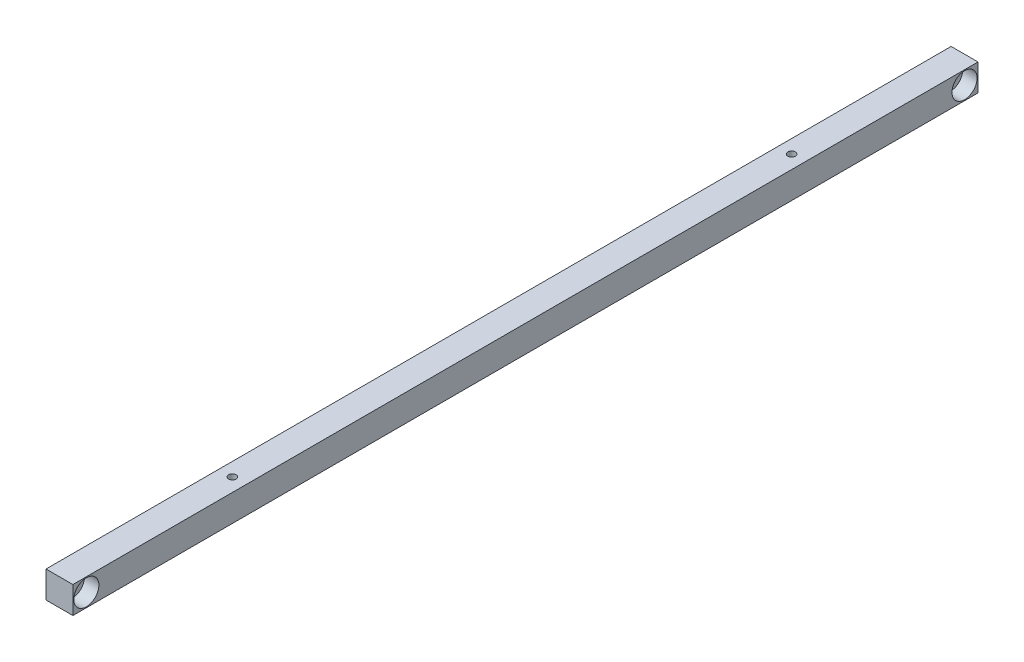
SolidWorks part; units mm, degrees
material "1.0715 (11SMn30)"
ref_plane "Ön Düzlem" through (0, 0, 0) normal (0, 0, 1) x (1, 0, 0)
ref_plane "Üst Düzlem" through (0, 0, 0) normal (0, 1, 0) x (1, 0, 0)
ref_plane "Sağ Düzlem" through (0, 0, 0) normal (1, 0, 0) x (0, 0, -1)
sketch "Çizim1" plane through (0, 0, 0) normal (0, 0, 1) x (1, 0, 0)
  line L1 (7.5, -7.5) -> (-7.5, -7.5)
  line L2 (7.5, -7.5) -> (7.5, 7.5)
  line L3 (7.5, 7.5) -> (-7.5, 7.5)
  line L4 (-7.5, -7.5) -> (-7.5, 7.5)
  line L5 (7.5, -7.5) -> (-7.5, 7.5) construction
  line L6 (7.5, 7.5) -> (-7.5, -7.5) construction
  point P0 (0, 0)
  dimension "D1" = 15
extrude "Yükseklik-Ekstrüzyon1" add sketch "Çizim1" along normal mid plane 505
hole_wizard "Delik1" positions "3B Çizim1" profile "Çizim4" legacy
sketch3d "3B Çizim1"
  line L1 (7.5, -7.5, 252.5) -> (7.5, -7.5, -252.5) construction
  line L2 (7.5, -7.5, -252.5) -> (7.5, 7.5, -252.5) construction
  point P21 (7.5, 0, -245)
  dimension "D1" = 7.5
  dimension "D2" = 7.5
sketch "Çizim4" plane through (7.5, 0, -245) normal (0, 1, 0) x (0, 0, -1)
  line L0 (0, 0) -> (0, 15)
  line L1 (0, 15) -> (4.25, 15)
  line L2 (4.25, 15) -> (4.25, 8)
  line L3 (4.25, 8) -> (7, 8)
  line L4 (7, 8) -> (7, 0)
  line L5 (7, 0) -> (0, 0)
  line L6 (0, 110) -> (0, -10) construction
  dimension "Diameter" = 8.5
  dimension "Depth" = 15
  dimension "C-Bore Diameter" = 14
  dimension "C-Bore Depth" = 8
mirror "Aynalama1" about plane through (0, 0, 0) normal (0, 0, 1) of "Delik1"
hole_wizard "M5 Dişli Delik1" positions "Çizim5" profile "Çizim6" tap size "M5" standard "ISO"
sketch "Çizim5" plane through (0, -7.5, 0) normal (0, -1, 0) x (-1, 0, 0)
  line L0 (0, 0) -> (40.6786, 0) construction
  point P0 (0, 155.9964)
  point P7 (0, -155.9964)
sketch "Çizim6" plane through (0, -7.5, -155.9964) normal (1, 0, 0) x (0, 0, -1)
  line L0 (0, 0) -> (0, 25.2618)
  line L1 (0, 25.2618) -> (2.1, 24)
  line L2 (2.1, 24) -> (2.1, 0.425)
  line L3 (2.1, 0.425) -> (2.525, 0)
  line L5 (2.525, 0) -> (0, 0)
  line L6 (-2.1, 0.425) -> (-2.525, 0) construction
  line L10 (0, 25.2618) -> (-2.1, 24) construction
  line L11 (0, -6.35) -> (0, 107.95) construction
  dimension "Tap Drill Dia." = 4.2
  dimension "Tap Drill Depth" = 24
  dimension "Near C'Sink Dia." = 5.05
  dimension "Near C'Sink Angle" = 90
  dimension "Drill Angle" = 118
cosmetic thread "Delik Dişi1" parameters "D1"=20, "D2"=5
cosmetic thread "Delik Dişi2" parameters "D1"=20, "D2"=5
